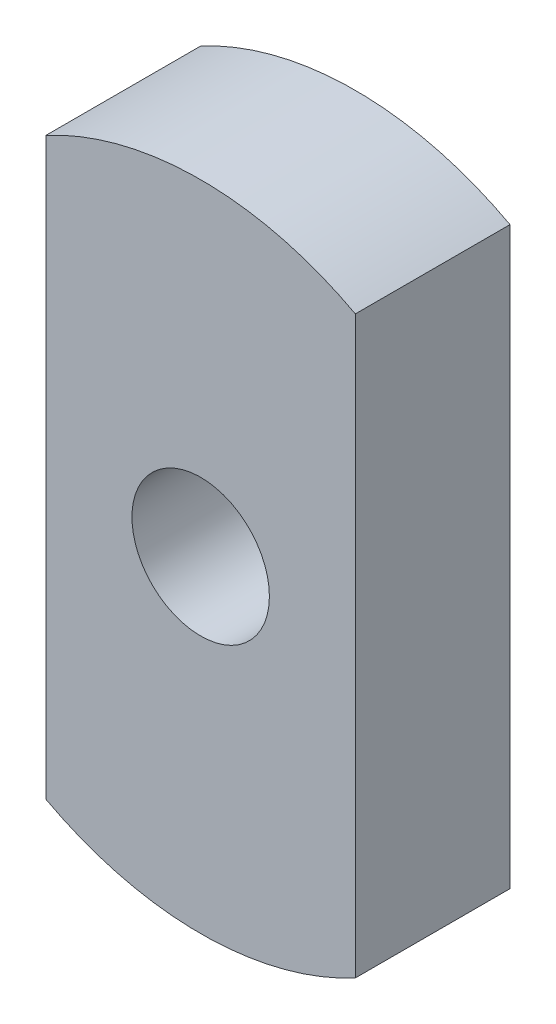
SolidWorks part; units mm, degrees
ref_plane "Front Plane" through (0, 0, 0) normal (0, 0, 1) x (1, 0, 0)
ref_plane "Top Plane" through (0, 0, 0) normal (0, 1, 0) x (1, 0, 0)
ref_plane "Right Plane" through (0, 0, 0) normal (1, 0, 0) x (0, 0, -1)
sketch "Sketch1" plane through (0, 0, 0) normal (0, 0, 1) x (1, 0, 0)
  line L0 (-4.5, 8.3666) -> (-4.5, -8.3666)
  line L1 (4.5, 8.3666) -> (4.5, -8.3666)
  circle A0 centre (0, 0) radius 9.5 construction
  circle A1 centre (0, 0) radius 2
  arc A2 (-4.5, 8.3666) -> (4.5, 8.3666) centre (0, 0) cw
  arc A3 (-4.5, -8.3666) -> (4.5, -8.3666) centre (0, 0) ccw
  dimension "D1" = 19
  dimension "D2" = 4
  dimension "D3" = 4.5
extrude "Boss-Extrude1" add sketch "Sketch1" along normal blind 4.5
